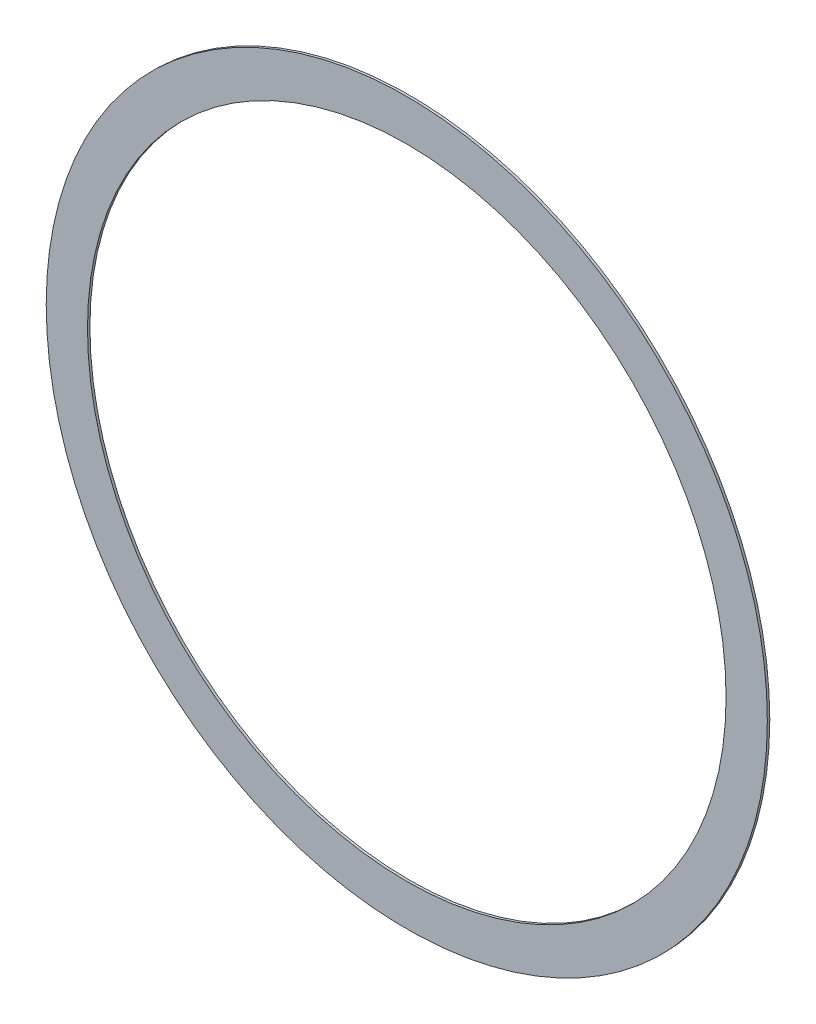
SolidWorks part; units mm, degrees
ref_plane "Front Plane" through (0, 0, 0) normal (0, 0, 1) x (1, 0, 0)
ref_plane "Top Plane" through (0, 0, 0) normal (0, 1, 0) x (1, 0, 0)
ref_plane "Right Plane" through (0, 0, 0) normal (1, 0, 0) x (0, 0, -1)
sketch "Sketch1" plane through (0, 0, 0) normal (0, 0, 1) x (1, 0, 0)
  circle A0 centre (0, 0) radius 65
  circle A1 centre (0, 0) radius 73.4
  dimension "D1" = 146.8
  dimension "D2" = 130
extrude "Boss-Extrude1" add sketch "Sketch1" along normal blind 0.5
